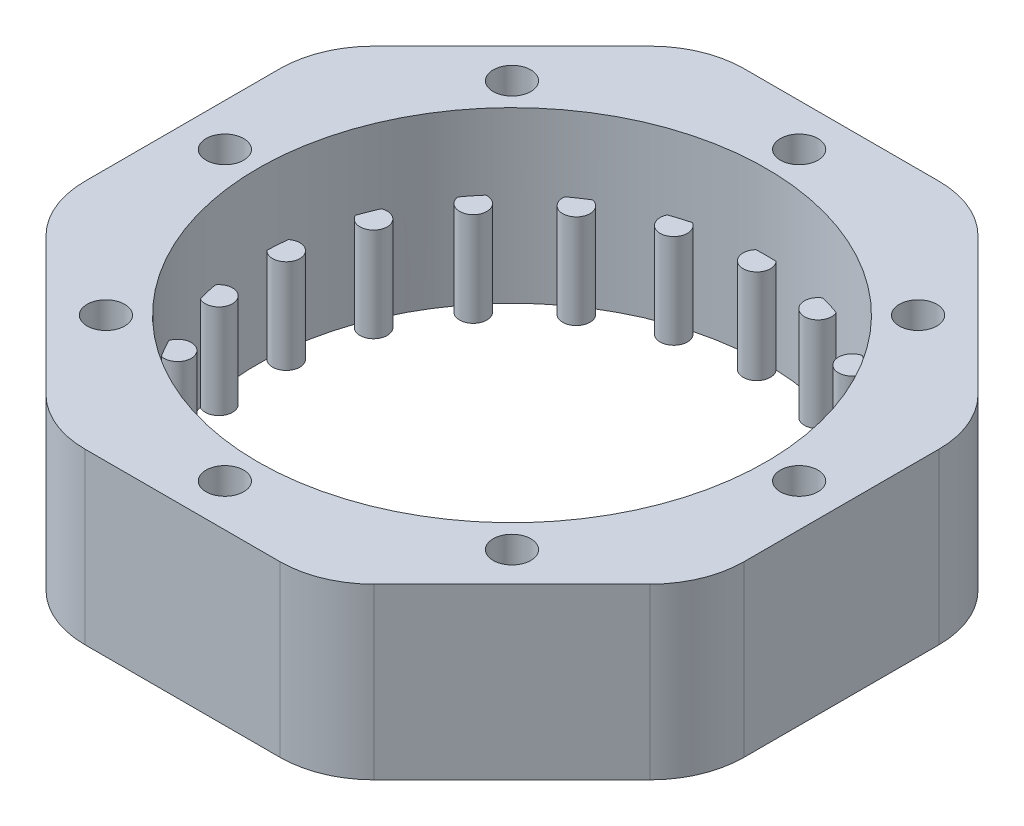
SolidWorks part; units mm, degrees
ref_plane "Front Plane" through (0, 0, 0) normal (0, 0, 1) x (1, 0, 0)
ref_plane "Top Plane" through (0, 0, 0) normal (0, 1, 0) x (1, 0, 0)
ref_plane "Right Plane" through (0, 0, 0) normal (1, 0, 0) x (0, 0, -1)
sketch "Sketch1" plane through (0, 0, 0) normal (0, 1, 0) x (1, 0, 0)
  line L0 (0, 0) -> (-26527.7717, 0) construction
  line L1 (0, 0) -> (0, -26527.7717) construction
  circle A0 centre (0, 0) radius 32
  circle A1 centre (0, 0) radius 27
  dimension "D1" = 64
  dimension "D2" = 54
extrude "Boss-Extrude1" add sketch "Sketch1" along normal blind 18
sketch "Sketch2" plane through (0, 0, 0) normal (0, 1, 0) x (1, 0, 0)
  line L0 (0, 0) -> (-50000, 0) construction
  line L1 (0, 0) -> (0, -50000) construction
  circle A0 centre (0, 0) radius 26 construction
  circle A1 centre (0, 26) radius 1.45
  circle A2 centre (7.6636, 24.8449) radius 1.45
  circle A3 centre (14.6463, 21.4822) radius 1.45
  circle A4 centre (20.3276, 16.2107) radius 1.45
  circle A5 centre (24.2027, 9.4989) radius 1.45
  circle A6 centre (25.9273, 1.943) radius 1.45
  circle A7 centre (25.3481, -5.7855) radius 1.45
  circle A8 centre (22.5167, -13) radius 1.45
  circle A9 centre (17.6845, -19.0593) radius 1.45
  circle A10 centre (11.281, -23.4252) radius 1.45
  circle A11 centre (3.8751, -25.7096) radius 1.45
  circle A12 centre (-3.8751, -25.7096) radius 1.45
  circle A13 centre (-11.281, -23.4252) radius 1.45
  circle A14 centre (-17.6845, -19.0593) radius 1.45
  circle A15 centre (-22.5167, -13) radius 1.45
  circle A16 centre (-25.3481, -5.7855) radius 1.45
  circle A17 centre (-25.9273, 1.943) radius 1.45
  circle A18 centre (-24.2027, 9.4989) radius 1.45
  circle A19 centre (-20.3276, 16.2107) radius 1.45
  circle A20 centre (-14.6463, 21.4822) radius 1.45
  circle A21 centre (-7.6636, 24.8449) radius 1.45
  point P42 (0, 0)
  dimension "D1" = 52
  dimension "D2" = 2.9
  dimension "D3" = 21
extrude "Boss-Extrude2" add sketch "Sketch2" along normal blind 10
sketch "Sketch4" plane through (0, 0, 0) normal (0, 1, 0) x (1, 0, 0)
  line L0 (0, 0) -> (-50000, 0) construction
  line L1 (0, 0) -> (0, -50000) construction
  line L10 (10.3553, 35) -> (-10.3553, 35)
  line L11 (-17.4264, 32.0711) -> (-32.0711, 17.4264)
  line L12 (-35, 10.3553) -> (-35, -10.3553)
  line L13 (35, 10.3553) -> (35, -10.3553)
  line L14 (17.4264, 32.0711) -> (32.0711, 17.4264)
  line L15 (17.4264, -32.0711) -> (32.0711, -17.4264)
  line L16 (-17.4264, -32.0711) -> (-32.0711, -17.4264)
  line L17 (10.3553, -35) -> (-10.3553, -35)
  circle A10 centre (0, 0) radius 32 construction
  circle A11 centre (0, 0) radius 32
  circle A12 centre (0, 0) radius 35 construction
  arc A13 (-32.0711, 17.4264) -> (-35, 10.3553) centre (-25, 10.3553) ccw
  arc A14 (-32.0711, -17.4264) -> (-35, -10.3553) centre (-25, -10.3553) cw
  arc A15 (-17.4264, -32.0711) -> (-10.3553, -35) centre (-10.3553, -25) ccw
  arc A16 (17.4264, -32.0711) -> (10.3553, -35) centre (10.3553, -25) cw
  arc A17 (32.0711, -17.4264) -> (35, -10.3553) centre (25, -10.3553) ccw
  arc A18 (35, 10.3553) -> (32.0711, 17.4264) centre (25, 10.3553) ccw
  arc A19 (17.4264, 32.0711) -> (10.3553, 35) centre (10.3553, 25) ccw
  arc A20 (-10.3553, 35) -> (-17.4264, 32.0711) centre (-10.3553, 25) ccw
  point P9 (0, -35)
  point P16 (0, 35)
  point P19 (35, 0)
  point P20 (-35, 0)
  point P23 (-35, 14.4975)
  point P26 (-35, -14.4975)
  point P29 (-14.4975, -35)
  point P32 (14.4975, -35)
  point P35 (35, -14.4975)
  point P38 (35, 14.4975)
  point P41 (14.4975, 35)
  point P44 (-14.4975, 35)
  dimension "D1" = 70
  dimension "D2" = 10
extrude "Boss-Extrude3" add sketch "Sketch4" along normal blind 18
sketch "Sketch5" plane through (0, 18, 0) normal (0, 1, 0) x (1, 0, 0)
  line L0 (0, 0) -> (-50000, 0) construction
  line L1 (0, 0) -> (0, -50000) construction
  line L2 (0, 0) -> (-35355.3391, 35355.3391) construction
  line L3 (-17.4264, 32.0711) -> (-32.0711, 17.4264) construction
  circle A0 centre (-21.5668, 21.5668) radius 2
  circle A1 centre (21.5668, 21.5668) radius 2
  circle A2 centre (21.5668, -21.5668) radius 2
  circle A3 centre (-21.5668, -21.5668) radius 2
  point P10 (-24.7487, 24.7487)
  point P22 (0, 0)
  dimension "D1" = 4.5
  dimension "D2" = 4
extrude "Cut-Extrude2" cut sketch "Sketch5" against normal through all
sketch "Sketch3" plane through (0, 18, 0) normal (0, 1, 0) x (1, 0, 0)
  line L0 (0, 0) -> (-50000, 0) construction
  line L1 (0, 0) -> (0, -50000) construction
  circle A0 centre (0, 0) radius 30.5 construction
  circle A1 centre (0, 30.5) radius 2
  circle A2 centre (30.5, 0) radius 2
  circle A3 centre (0, -30.5) radius 2
  circle A4 centre (-30.5, 0) radius 2
  point P19 (0, 0)
  dimension "D1" = 61
  dimension "D2" = 4
  dimension "D3" = 4
extrude "Cut-Extrude3" cut sketch "Sketch3" against normal through all
